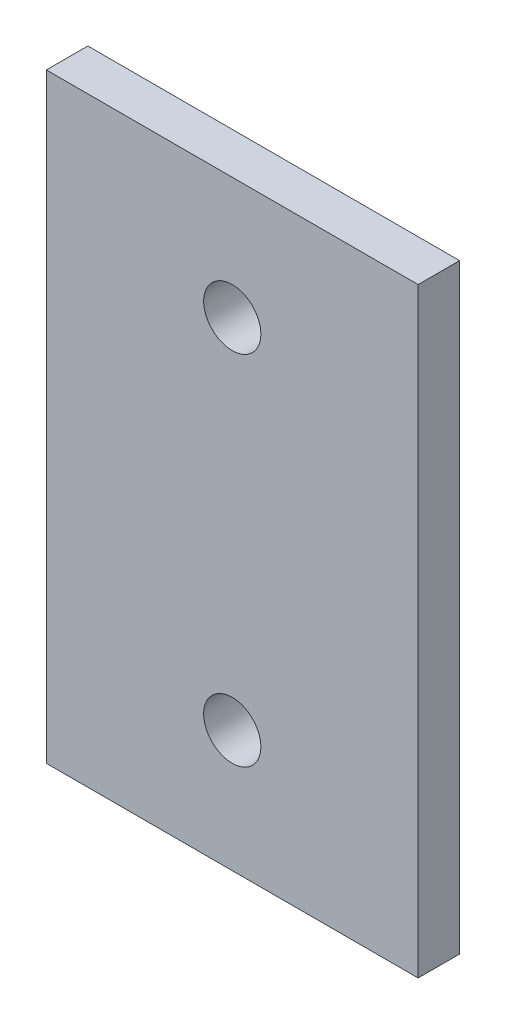
SolidWorks part; units mm, degrees
material "Бальса"
ref_plane "Спереди" through (0, 0, 0) normal (0, 0, 1) x (1, 0, 0)
ref_plane "Сверху" through (0, 0, 0) normal (0, 1, 0) x (1, 0, 0)
ref_plane "Справа" through (0, 0, 0) normal (1, 0, 0) x (0, 0, -1)
sketch "Эскиз1" plane through (0, 0, 0) normal (0, 0, 1) x (1, 0, 0)
  line L0 (26, 84) -> (26, 0) construction
  line L1 (0, 0) -> (52, 0)
  line L2 (0, 0) -> (0, 84)
  line L3 (0, 84) -> (52, 84)
  line L4 (52, 0) -> (52, 84)
  line L5 (26, 42) -> (52, 42) construction
  circle A0 centre (26, 67) radius 4
  circle A1 centre (26, 17) radius 4
  dimension "D3" = 50
  dimension "D4" = 25
  dimension "D5" = 8
  dimension "D1" = 52
  dimension "D2" = 84
extrude "Бобышка-Вытянуть1" add sketch "Эскиз1" along normal blind 5.8
